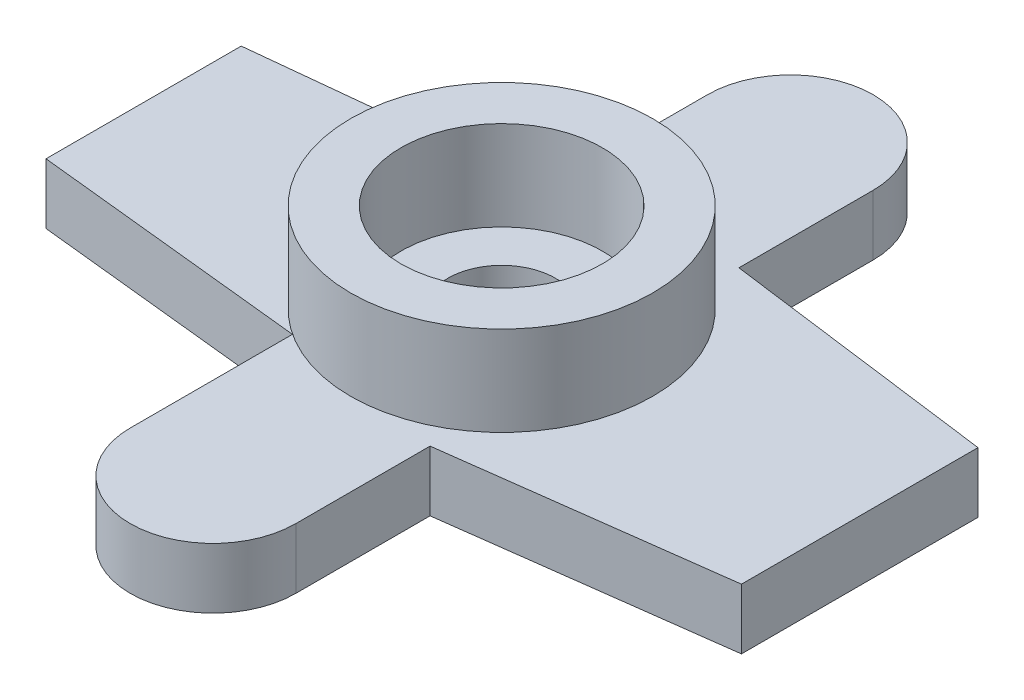
SolidWorks part; units mm, degrees
ref_plane "Piano frontale" through (0, 0, 0) normal (0, 0, 1) x (1, 0, 0)
ref_plane "Piano superiore" through (0, 0, 0) normal (0, 1, 0) x (1, 0, 0)
ref_plane "Piano destro" through (0, 0, 0) normal (1, 0, 0) x (0, 0, -1)
sketch "Schizzo1" plane through (0, 0, 0) normal (0, 1, 0) x (1, 0, 0)
  line L0 (-1.8466, 2.825) -> (-14.5, 1.5)
  line L1 (-1.8466, -2.825) -> (-14.5, -1.5)
  line L2 (-1.8466, 2.825) -> (-1.8466, -2.825)
  line L3 (0, -6.45) -> (0, 6.45) construction
  line L4 (1.85, 3.45) -> (1.85, -3.45)
  line L5 (1.85, -3.45) -> (16.7, -1.5)
  line L6 (1.85, 3.45) -> (16.7, 1.5)
  line L7 (-1.85, -6.45) -> (-1.85, 6.45)
  line L8 (1.85, -6.45) -> (1.85, 6.45)
  line L9 (8, -2.6424) -> (8, 2.6424)
  line L10 (-8, -2.1806) -> (-8, 2.1806)
  circle A0 centre (0, 0) radius 3.375
  arc A1 (-14.5, 1.5) -> (-14.5, -1.5) centre (-14.5, 0) ccw
  arc A2 (16.7, 1.5) -> (16.7, -1.5) centre (16.7, 0) cw
  arc A3 (-1.85, -6.45) -> (1.85, -6.45) centre (0, -6.45) ccw
  arc A4 (1.85, 6.45) -> (-1.85, 6.45) centre (0, 6.45) ccw
  point P8 (-1.8466, 0)
  point P14 (18.2, 0)
  point P18 (1.85, 0)
  point P19 (0, 0)
  point P25 (-16, 0)
  point P31 (0, 8.3)
  point P32 (0, -8.3)
  dimension "D1" = 6.75
  dimension "D3" = 1.5
  dimension "D7" = 1.5
  dimension "D2" = 5.65
  dimension "D4" = 3
  dimension "D5" = 16
  dimension "D6" = 6.9
  dimension "D8" = 3
  dimension "D9" = 34.2
  dimension "D10" = 3.7
  dimension "D11" = 16.6
  dimension "D12" = 8
  dimension "D13" = 8
extrude "Estrusione-Estrusione1" add sketch "Schizzo1" along normal blind 1.35
sketch "Schizzo2" plane through (0, 1.35, 0) normal (0, 1, 0) x (1, 0, 0)
  circle A0 centre (0, 0) radius 3.375
  dimension "D1" = 6.75
extrude "Estrusione-Estrusione2" add sketch "Schizzo2" along normal blind 2
sketch "Schizzo3" plane through (0, 3.35, 0) normal (0, 1, 0) x (1, 0, 0)
  circle A0 centre (0, 0) radius 2.25
  dimension "D1" = 4.5
extrude "Taglio-Estrusione1" cut sketch "Schizzo3" against normal blind 2
sketch "Schizzo4" plane through (0, 1.35, 0) normal (0, 1, 0) x (1, 0, 0)
  circle A0 centre (0, 0) radius 1.2
  dimension "D1" = 2.4
extrude "Taglio-Estrusione2" cut sketch "Schizzo4" against normal through all
